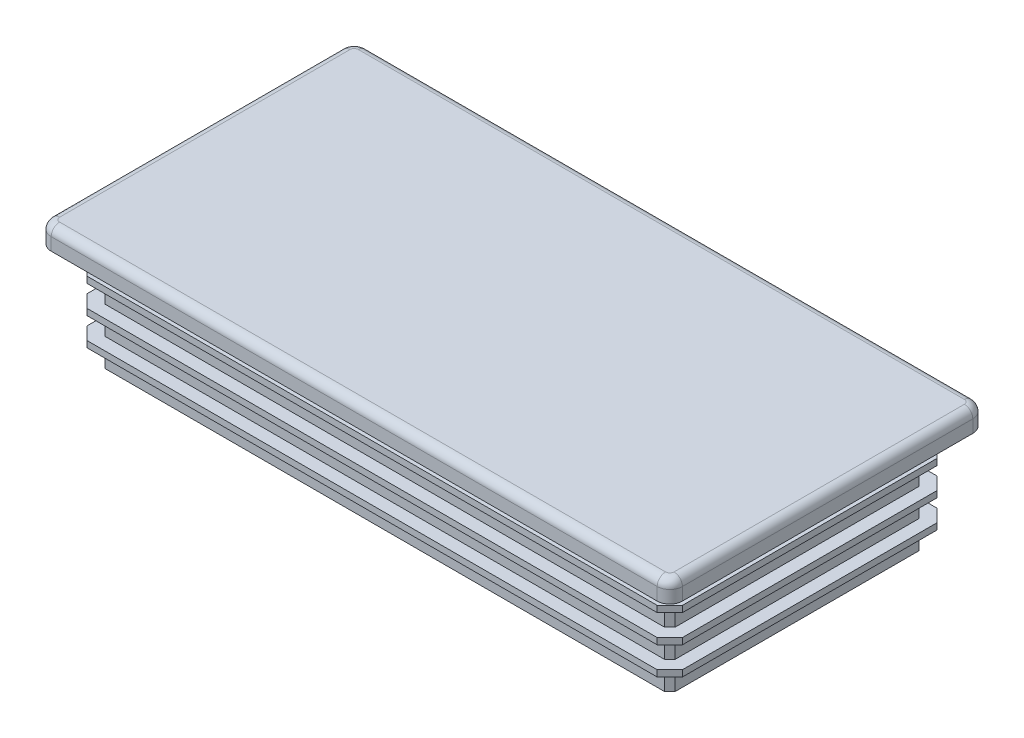
SolidWorks part; units mm, degrees
material "ABS"
ref_plane "Front" through (0, 0, 0) normal (0, 0, 1) x (1, 0, 0)
ref_plane "Top" through (0, 0, 0) normal (0, 1, 0) x (1, 0, 0)
ref_plane "Right" through (0, 0, 0) normal (1, 0, 0) x (0, 0, -1)
sketch "Sketch5" plane through (0, 0, 0) normal (0, 0, 1) x (1, 0, 0)
  line L0 (0, 0) -> (0, 12.7) construction
  dimension "Height" = 12.7
sketch "Sketch1" plane through (0, 0, 0) normal (0, 1, 0) x (1, 0, 0)
  line L1 (-35.941, 16.891) -> (35.941, 16.891)
  line L2 (-35.941, 16.891) -> (-35.941, -16.891)
  line L3 (-35.941, -16.891) -> (35.941, -16.891)
  line L4 (35.941, 16.891) -> (35.941, -16.891)
  line L5 (-35.941, 16.891) -> (35.941, -16.891) construction
  line L6 (-35.941, -16.891) -> (35.941, 16.891) construction
  line L21 (38.1, 19.05) -> (-38.1, 19.05) construction
  line L22 (38.1, 19.05) -> (38.1, -19.05) construction
  line L23 (38.1, -19.05) -> (-38.1, -19.05) construction
  line L24 (-38.1, 19.05) -> (-38.1, -19.05) construction
  line L25 (38.1, 19.05) -> (-38.1, -19.05) construction
  line L26 (38.1, -19.05) -> (-38.1, 19.05) construction
  point P0 (0, 0)
  point P6 (0, 0)
  point P11 (0, 0)
  point P22 (0, 0)
  dimension "For Inside Length Max" = 71.882
  dimension "For Inside Width Max" = 33.782
  dimension "Head Length" = 76.2
  dimension "Head Width" = 38.1
extrude "Boss-Extrude1" add sketch "Sketch1" along normal up to vertex (12.7 mm away) up to point (0, 12.7, 0)
sketch "Sketch2" plane through (0, 12.7, 0) normal (0, 1, 0) x (1, 0, 0)
  line L0 (-38.1, 19.05) -> (-38.1, -19.05) construction
  line L1 (38.1, 19.05) -> (-38.1, 19.05) construction
  line L2 (38.1, 19.05) -> (38.1, -19.05) construction
  line L3 (38.1, -19.05) -> (-38.1, -19.05) construction
  line L4 (-38.1, 17.526) -> (-38.1, -17.526)
  line L5 (36.576, 19.05) -> (-36.576, 19.05)
  line L6 (38.1, 17.526) -> (38.1, -17.526)
  line L7 (36.576, -19.05) -> (-36.576, -19.05)
  arc A0 (-38.1, -17.526) -> (-36.576, -19.05) centre (-36.576, -17.526) ccw
  arc A1 (38.1, -17.526) -> (36.576, -19.05) centre (36.576, -17.526) cw
  arc A2 (36.576, 19.05) -> (38.1, 17.526) centre (36.576, 17.526) cw
  arc A3 (-38.1, 17.526) -> (-36.576, 19.05) centre (-36.576, 17.526) cw
  dimension "D1" = 1.524
extrude "Boss-Extrude2" add sketch "Sketch2" along normal blind 2.54
chamfer "Chamfer1" distance 1.524 angle 45 4 edges at (35.941, 6.35, -16.891) (35.941, 6.35, 16.891) (-35.941, 6.35, -16.891) (-35.941, 6.35, 16.891)
shell "Shell1" thickness 2.54
sketch "Sketch3" plane through (0, 0, 0) normal (0, -1, 0) x (-1, 0, 0)
  line L4 (-35.941, 15.367) -> (-35.941, -15.367)
  line L5 (-35.941, 15.367) -> (-35.941, -15.367)
  line L6 (-34.417, -16.891) -> (34.417, -16.891)
  line L7 (-34.417, -16.891) -> (34.417, -16.891)
  line L8 (35.941, -15.367) -> (35.941, 15.367)
  line L9 (35.941, -15.367) -> (35.941, 15.367)
  line L10 (34.417, 16.891) -> (-34.417, 16.891)
  line L11 (34.417, 16.891) -> (-34.417, 16.891)
  line L16 (-34.417, 16.891) -> (-35.941, 15.367)
  line L17 (-34.417, 16.891) -> (-35.941, 15.367)
  line L18 (-35.941, -15.367) -> (-34.417, -16.891)
  line L19 (-35.941, -15.367) -> (-34.417, -16.891)
  line L20 (34.417, -16.891) -> (35.941, -15.367)
  line L21 (34.417, -16.891) -> (35.941, -15.367)
  line L22 (35.941, 15.367) -> (34.417, 16.891)
  line L23 (35.941, 15.367) -> (34.417, 16.891)
  dimension "D1" = 0
sketch "Sketch4" plane through (0, 0, 0) normal (0, 0, 1) x (1, 0, 0)
  line L1 (35.941, 2.6035) -> (34.417, 2.6035)
  line L2 (35.941, 2.6035) -> (35.941, 0)
  line L3 (35.941, 0) -> (34.417, 0)
  line L4 (34.417, 2.6035) -> (34.417, 0)
  line L5 (38.1, 0) -> (-38.1, 0) construction
  line L6 (-36.576, 12.7) -> (36.576, 12.7) construction
  line L7 (35.941, 9.3345) -> (34.417, 9.3345)
  line L8 (35.941, 9.3345) -> (35.941, 6.731)
  line L9 (35.941, 6.731) -> (34.417, 6.731)
  line L10 (34.417, 9.3345) -> (34.417, 6.731)
  line L11 (35.941, 10.0965) -> (34.417, 10.0965)
  line L12 (35.941, 10.0965) -> (35.941, 12.7)
  line L13 (35.941, 12.7) -> (34.417, 12.7)
  line L14 (34.417, 10.0965) -> (34.417, 12.7)
  line L15 (35.941, 10.0965) -> (35.941, 9.3345) construction
  line L16 (34.417, 5.969) -> (35.941, 5.969)
  line L17 (34.417, 5.969) -> (34.417, 3.3655)
  line L18 (34.417, 3.3655) -> (35.941, 3.3655)
  line L19 (35.941, 5.969) -> (35.941, 3.3655)
  line L20 (35.941, 6.731) -> (35.941, 5.969) construction
  line L21 (35.941, 3.3655) -> (35.941, 2.6035) construction
  line L22 (35.941, 12.7) -> (35.941, 0) construction
  line L23 (36.576, 12.7) -> (38.1, 12.7) construction
  line L26 (34.417, 0) -> (34.417, 12.7) construction
  dimension "D1" = 0.762
sweep "Cut-Sweep2" cut profiles "Sketch4" path "Sketch3"
fillet "Fillet2" radius 1.016 8 edges at (-38.1, 15.24, 0) (-37.6536, 15.24, -18.6036) (0, 15.24, -19.05) (37.6536, 15.24, -18.6036) (38.1, 15.24, 0) (37.6536, 15.24, 18.6036) (0, 15.24, 19.05) (-37.6536, 15.24, 18.6036)
